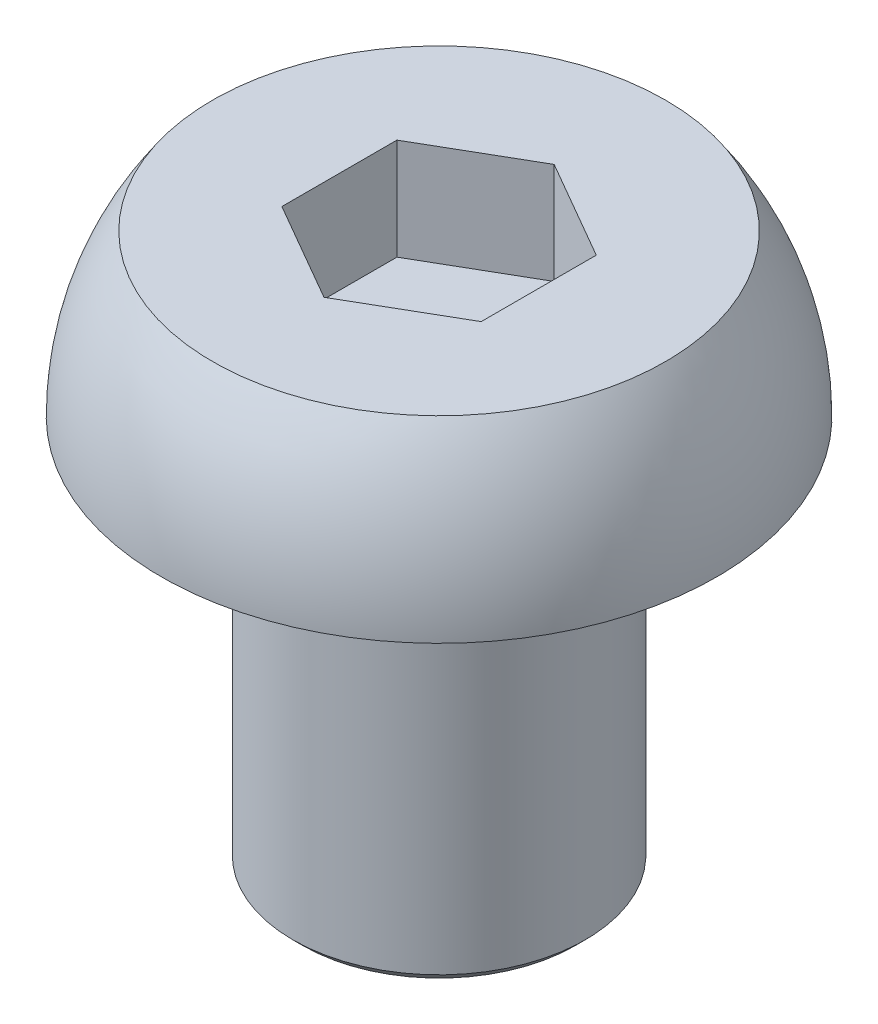
SolidWorks part; units mm, degrees
material "Q235"
ref_plane "前视基准面" through (0, 0, 0) normal (0, 0, 1) x (1, 0, 0)
ref_plane "上视基准面" through (0, 0, 0) normal (0, 1, 0) x (1, 0, 0)
ref_plane "右视基准面" through (0, 0, 0) normal (1, 0, 0) x (0, 0, -1)
sketch "草图1" plane through (0, 0, 0) normal (0, 0, 1) x (1, 0, 0)
  line L0 (0, 0) -> (0, 1.65) construction
  line L1 (0, 0) -> (2.85, 0)
  line L2 (0, 1.65) -> (2.3238, 1.65)
  line L3 (0, 0) -> (0, 1.65)
  arc A0 (2.85, 0) -> (2.3238, 1.65) centre (0, 0) ccw
  dimension "D1" = 5.7
  dimension "D2" = 1.65
revolve "圆头部分" add sketch "草图1" angle 360 about L0
sketch "草图2" plane through (0, 0, 0) normal (0, -1, 0) x (1, 0, 0)
  circle A0 centre (0, 0) radius 1.5
  dimension "D1" = 3
extrude "螺柱部分" add sketch "草图2" along normal blind 4
cosmetic thread "装饰螺纹线1" parameters "D2"=2.459
sketch "草图3" plane through (0, 1.65, 0) normal (0, 1, 0) x (1, 0, 0)
  line L1 (1.0225, -0.5903) -> (1.0225, 0.5903)
  line L2 (1.0225, 0.5903) -> (0, 1.1807)
  line L3 (0, 1.1807) -> (-1.0225, 0.5903)
  line L4 (-1.0225, 0.5903) -> (-1.0225, -0.5903)
  line L5 (-1.0225, -0.5903) -> (0, -1.1807)
  line L6 (0, -1.1807) -> (1.0225, -0.5903)
  circle A0 centre (0, 0) radius 1.0225 construction
  dimension "D1" = 2.045
extrude "沉头内六角" cut sketch "草图3" against normal blind 1.04
chamfer "修饰性倒角" distance 0.1 angle 45 1 edges at (0, -4, -1.5)
